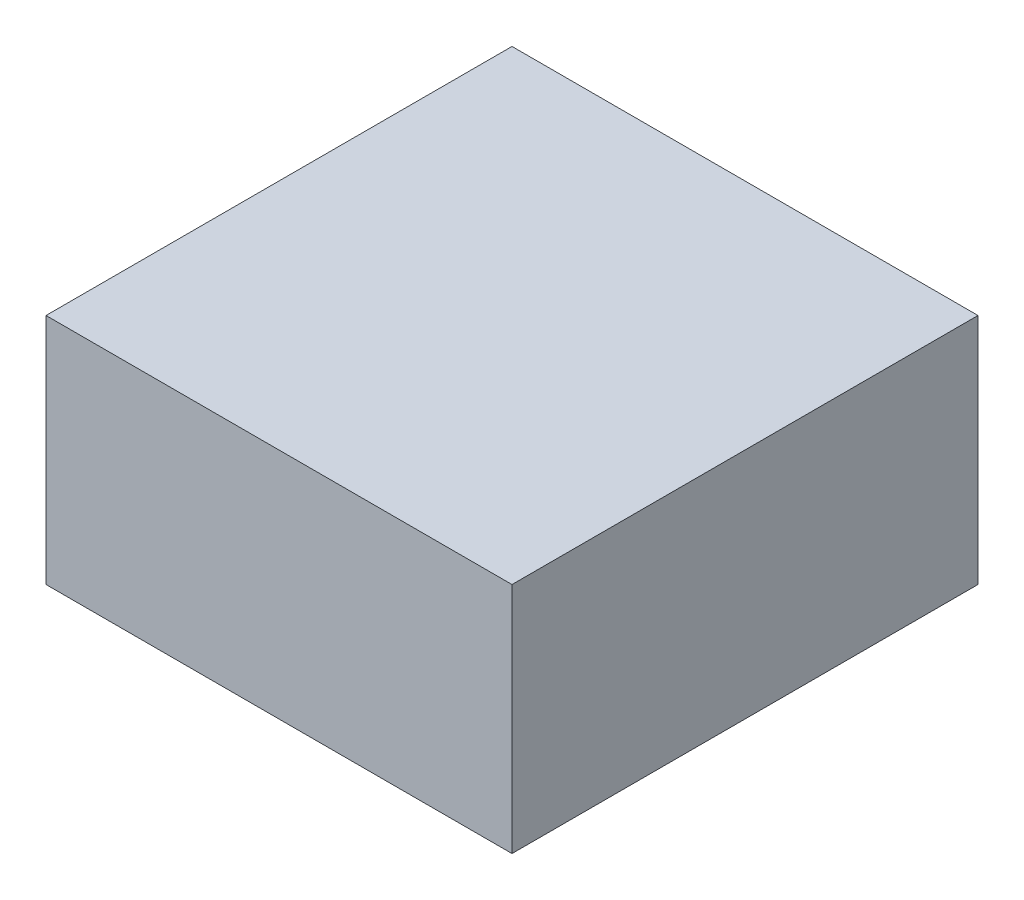
SolidWorks part; units mm, degrees
ref_plane "Front Plane" through (0, 0, 0) normal (0, 0, 1) x (1, 0, 0)
ref_plane "Top Plane" through (0, 0, 0) normal (0, 1, 0) x (1, 0, 0)
ref_plane "Right Plane" through (0, 0, 0) normal (1, 0, 0) x (0, 0, -1)
sketch "Sketch1" plane through (0, 0, 0) normal (0, 1, 0) x (1, 0, 0)
  line L1 (-5, -5) -> (5, -5)
  line L2 (-5, -5) -> (-5, 5)
  line L3 (-5, 5) -> (5, 5)
  line L4 (5, -5) -> (5, 5)
  line L5 (-5, -5) -> (5, 5) construction
  line L6 (-5, 5) -> (5, -5) construction
  point P0 (0, 0)
  dimension "D1" = 10
  dimension "D2" = 10
extrude "Boss-Extrude1" add sketch "Sketch1" along normal blind 5
